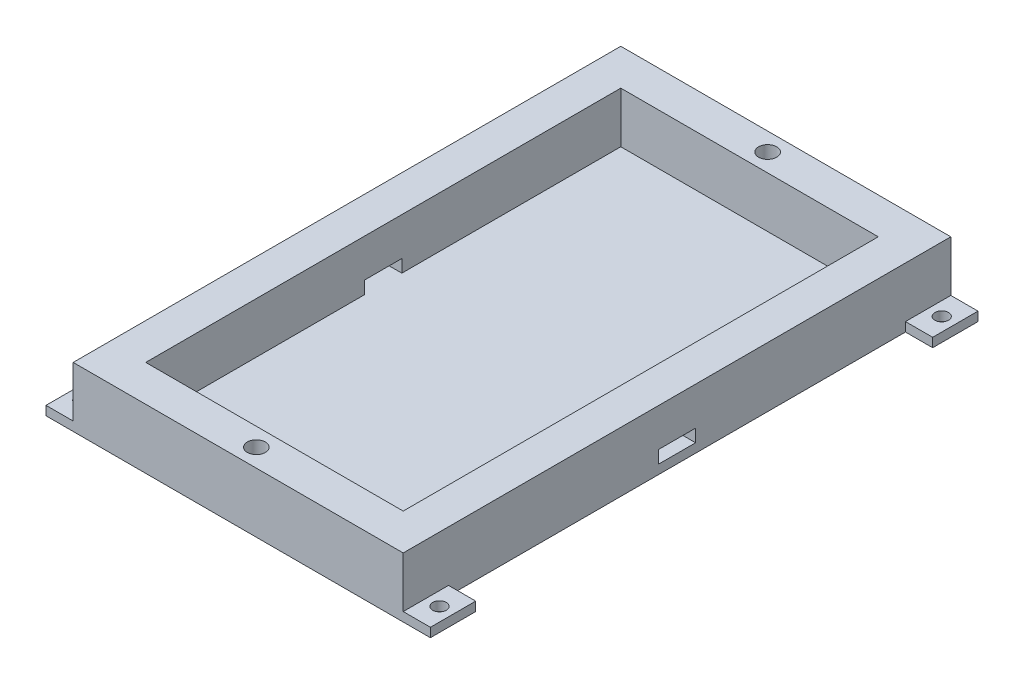
SolidWorks part; units mm, degrees
ref_plane "Plano frontal" through (0, 0, 0) normal (0, 0, 1) x (1, 0, 0)
ref_plane "Plano superior" through (0, 0, 0) normal (0, 1, 0) x (1, 0, 0)
ref_plane "Plano direito" through (0, 0, 0) normal (1, 0, 0) x (0, 0, -1)
sketch "Esboço1" plane through (0, 0, 0) normal (0, 1, 0) x (1, 0, 0)
  line L1 (-14.2, 26.2) -> (14.2, 26.2)
  line L2 (-14.2, 26.2) -> (-14.2, -26.2)
  line L3 (-14.2, -26.2) -> (14.2, -26.2)
  line L4 (14.2, 26.2) -> (14.2, -26.2)
  line L5 (-14.2, 26.2) -> (14.2, -26.2) construction
  line L6 (-14.2, -26.2) -> (14.2, 26.2) construction
  line L7 (-18.2, 30.2) -> (18.2, 30.2)
  line L8 (-18.2, 30.2) -> (-18.2, -30.2)
  line L9 (-18.2, -30.2) -> (18.2, -30.2)
  line L10 (18.2, 30.2) -> (18.2, -30.2)
  line L11 (-18.2, 30.2) -> (18.2, -30.2) construction
  line L12 (-18.2, -30.2) -> (18.2, 30.2) construction
  point P0 (0, 0)
  point P6 (0, 0)
  dimension "D1" = 52.4
  dimension "D2" = 28.4
  dimension "D3" = 60.4
  dimension "D4" = 36.4
extrude "Ressalto-extrusão1" add sketch "Esboço1" along normal blind 6.6
sketch "Esboço2" plane through (0, 0, 0) normal (0, 1, 0) x (1, 0, 0)
  line L1 (14.2, -26.2) -> (-14.2, -26.2)
  line L2 (14.2, -26.2) -> (14.2, 26.2)
  line L3 (14.2, 26.2) -> (-14.2, 26.2)
  line L4 (-14.2, -26.2) -> (-14.2, 26.2)
  line L5 (14.2, -26.2) -> (-14.2, 26.2) construction
  line L6 (14.2, 26.2) -> (-14.2, -26.2) construction
  point P0 (0, 0)
extrude "Ressalto-extrusão2" add sketch "Esboço2" along normal blind 1
sketch "Esboço4" plane through (18.2, 0, 0) normal (1, 0, 0) x (0, 0, -1)
  line L0 (-26.2, 1) -> (26.2, 1) construction
  line L1 (2.05, 1) -> (-2.05, 1)
  line L2 (2.05, 1) -> (2.05, 2.4)
  line L3 (2.05, 2.4) -> (-2.05, 2.4)
  line L4 (-2.05, 1) -> (-2.05, 2.4)
  dimension "D1" = 4.1
  dimension "D2" = 1.4
  dimension "D3" = 2.05
extrude "Corte-extrusão2" cut sketch "Esboço4" against normal blind 38
sketch "Esboço5" plane through (0, 0, 0) normal (0, 1, 0) x (1, 0, 0)
  line L1 (-18.2, 30.2) -> (-21.2, 30.2)
  line L2 (-18.2, 30.2) -> (-18.2, 25.2)
  line L3 (-18.2, 25.2) -> (-21.2, 25.2)
  line L4 (-21.2, 30.2) -> (-21.2, 25.2)
  line L5 (-18.2, -30.2) -> (-21.2, -30.2)
  line L6 (-18.2, -30.2) -> (-18.2, -25.2)
  line L7 (-18.2, -25.2) -> (-21.2, -25.2)
  line L8 (-21.2, -30.2) -> (-21.2, -25.2)
  line L9 (18.2, -30.2) -> (21.2, -30.2)
  line L10 (18.2, -30.2) -> (18.2, -25.2)
  line L11 (18.2, -25.2) -> (21.2, -25.2)
  line L12 (21.2, -30.2) -> (21.2, -25.2)
  line L13 (18.2, 30.2) -> (21.2, 30.2)
  line L14 (18.2, 30.2) -> (18.2, 25.2)
  line L15 (18.2, 25.2) -> (21.2, 25.2)
  line L16 (21.2, 30.2) -> (21.2, 25.2)
  circle A0 centre (-19.7, 27.7) radius 0.75
  circle A1 centre (19.7, 27.7) radius 0.75
  circle A2 centre (19.7, -27.7) radius 0.75
  circle A3 centre (-19.7, -27.7) radius 0.75
  point P20 (19.7, -27.7)
  dimension "D9" = 1.5
  dimension "D1" = 3
  dimension "D2" = 5
  dimension "D3" = 3
  dimension "D4" = 5
  dimension "D5" = 3
  dimension "D6" = 3
  dimension "D7" = 5
  dimension "D8" = 5
extrude "Ressalto-extrusão3" add sketch "Esboço5" along normal blind 1
sketch "Esboço6" plane through (0, 6.6, 0) normal (0, 1, 0) x (1, 0, 0)
  circle A0 centre (0, 28.2) radius 1
  circle A1 centre (0, -28.2) radius 1
  dimension "D1" = 2
  dimension "D2" = 2
extrude "Corte-extrusão3" cut sketch "Esboço6" against normal blind 4
